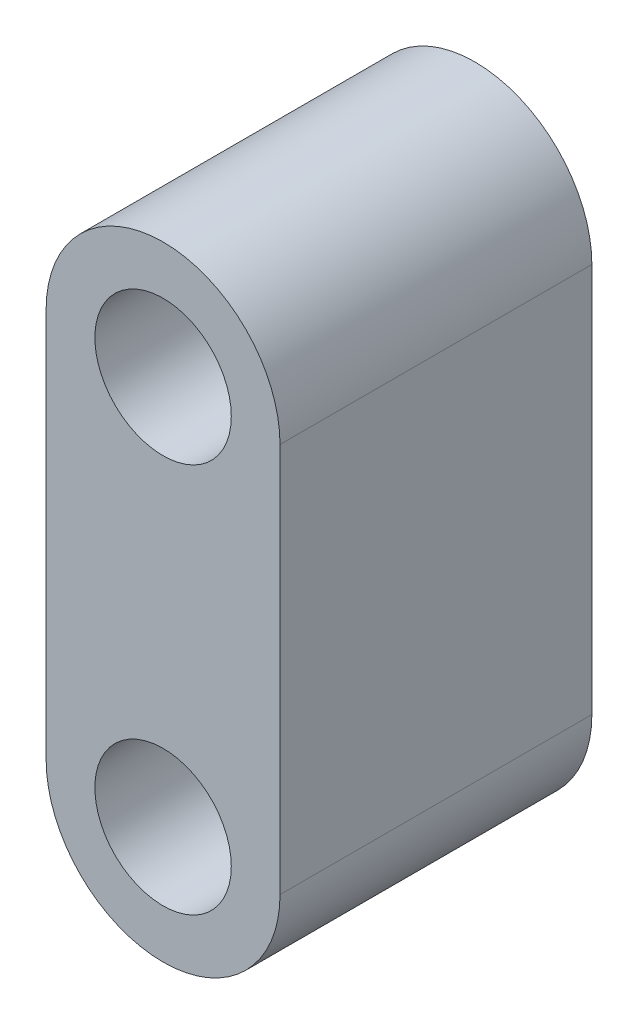
SolidWorks part; units mm, degrees
ref_plane "Front Plane" through (0, 0, 0) normal (0, 0, 1) x (1, 0, 0)
ref_plane "Top Plane" through (0, 0, 0) normal (0, 1, 0) x (1, 0, 0)
ref_plane "Right Plane" through (0, 0, 0) normal (1, 0, 0) x (0, 0, -1)
sketch "Sketch1" plane through (0, 0, 0) normal (0, 0, 1) x (1, 0, 0)
  line L2 (-3, 5) -> (-3, -5)
  line L4 (3, 5) -> (3, -5)
  arc A0 (3, 5) -> (-3, 5) centre (0, 5) ccw
  arc A1 (-3, -5) -> (3, -5) centre (0, -5) ccw
  point P7 (-3, 0)
  point P11 (3, 0)
  dimension "D2" = 6
  dimension "D1" = 10
extrude "Boss-Extrude1" add sketch "Sketch1" along normal blind 8 contours A0 L2 A1 L4
sketch "Schizzo1" plane through (0, 0, 8) normal (0, 0, 1) x (1, 0, 0)
  circle A0 centre (0, 5) radius 1.75
  point P2 (0, 0)
  point P5 (0, 0)
  dimension "D1" = 3.5
extrude "Taglio-Estrusione1" cut sketch "Schizzo1" against normal up to surface (8 mm away) up to face at (0, 0, 0)
mirror "Specchia1" about plane through (0, 0, 0) normal (0, 1, 0) of "Taglio-Estrusione1"
